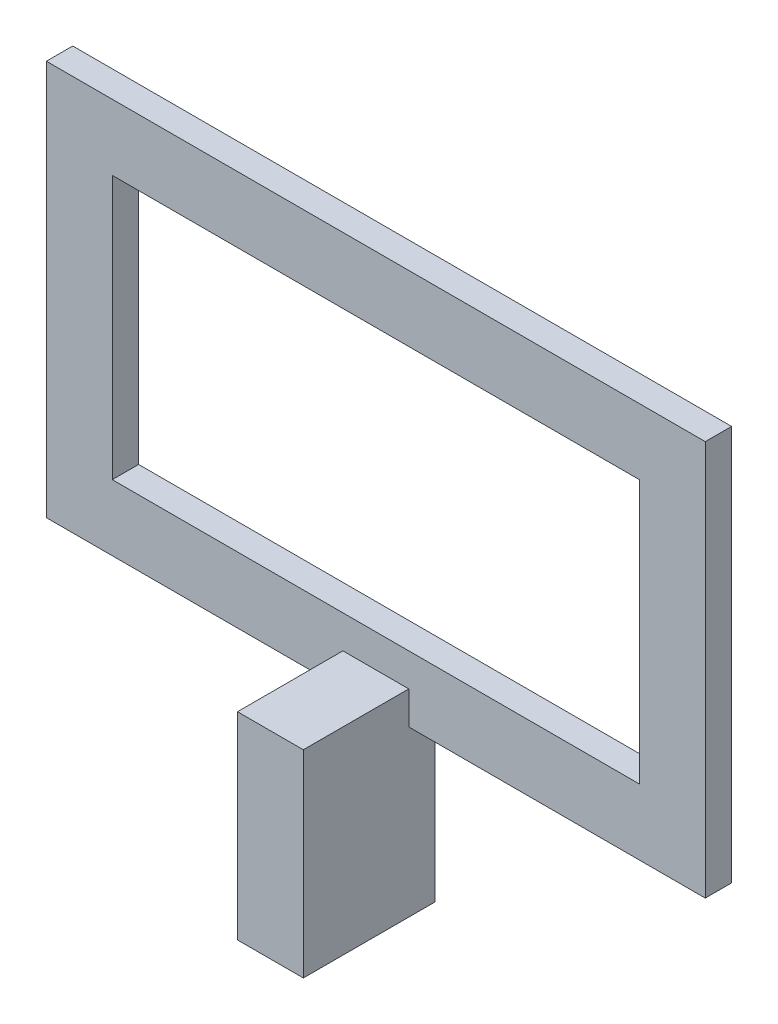
SolidWorks part; units mm, degrees
ref_plane "前视基准面" through (0, 0, 0) normal (0, 0, 1) x (1, 0, 0)
ref_plane "上视基准面" through (0, 0, 0) normal (0, 1, 0) x (1, 0, 0)
ref_plane "右视基准面" through (0, 0, 0) normal (1, 0, 0) x (0, 0, -1)
other "Configuration Table"
sketch "草图1" plane through (0, 0, 0) normal (0, 0, 1) x (1, 0, 0)
  line L1 (-250, -150) -> (250, -150)
  line L2 (-250, -150) -> (-250, 150)
  line L3 (-250, 150) -> (250, 150)
  line L4 (250, -150) -> (250, 150)
  line L5 (-250, -150) -> (250, 150) construction
  line L6 (-250, 150) -> (250, -150) construction
  point P0 (0, 0)
extrude "凸台-拉伸1" add sketch "草图1" along normal blind 20
sketch "草图2" plane through (0, 0, 0) normal (0, 0, 1) x (1, 0, 0)
  line L1 (-225, -125) -> (225, -125)
  line L2 (-225, -125) -> (-225, 125)
  line L3 (-225, 125) -> (225, 125)
  line L4 (225, -125) -> (225, 125)
  line L5 (-225, -125) -> (225, 125) construction
  line L6 (-225, 125) -> (225, -125) construction
  point P0 (0, 0)
extrude "凸台-拉伸2" add sketch "草图2" along normal blind 10
sketch "草图3" plane through (0, 0, 0) normal (0, 0, 1) x (1, 0, 0)
  line L1 (-200, -100) -> (200, -100)
  line L2 (-200, -100) -> (-200, 100)
  line L3 (-200, 100) -> (200, 100)
  line L4 (200, -100) -> (200, 100)
  line L5 (-200, -100) -> (200, 100) construction
  line L6 (-200, 100) -> (200, -100) construction
  point P0 (0, 0)
extrude "切除-拉伸1" cut sketch "草图3" along normal through all
sketch "草图4" plane through (0, 0, 0) normal (0, 0, 1) x (1, 0, 0)
  line L1 (-25, -275) -> (25, -275)
  line L2 (-25, -275) -> (-25, -125)
  line L3 (-25, -125) -> (25, -125)
  line L4 (25, -275) -> (25, -125)
  line L5 (-25, -275) -> (25, -125) construction
  line L6 (-25, -125) -> (25, -275) construction
  point P0 (0, -200)
extrude "凸台-拉伸3" add sketch "草图4" along normal blind 100
